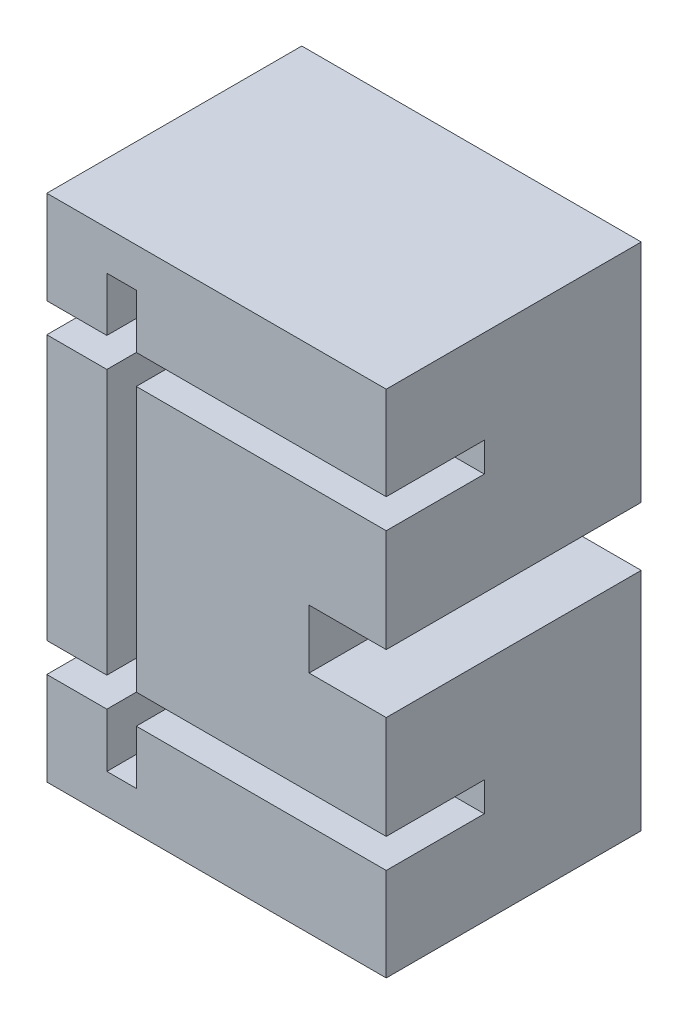
SolidWorks part; units mm, degrees
ref_plane "Ön Düzlem" through (0, 0, 0) normal (0, 0, 1) x (1, 0, 0)
ref_plane "Üst Düzlem" through (0, 0, 0) normal (0, 1, 0) x (1, 0, 0)
ref_plane "Sağ Düzlem" through (0, 0, 0) normal (1, 0, 0) x (0, 0, -1)
sketch "Sketch1" plane through (0, 0, 0) normal (0, 0, 1) x (1, 0, 0)
  line L0 (8.5625, 14.5) -> (-8.5625, 14.5)
  line L1 (8.5625, 14.5) -> (8.5625, 13)
  line L2 (8.5625, -14.5) -> (-8.5625, -14.5)
  line L3 (-8.5625, 14.5) -> (-8.5625, -14.5)
  line L4 (8.5625, 14.5) -> (-8.5625, -14.5) construction
  line L5 (8.5625, -14.5) -> (-8.5625, 14.5) construction
  line L6 (7.0625, 13) -> (-7.0625, 13)
  line L7 (-7.0625, 13) -> (-7.0625, -13)
  line L8 (7.0625, -13) -> (-7.0625, -13)
  line L9 (8.5625, -13) -> (8.5625, -14.5)
  line L10 (7.0625, -13) -> (8.5625, -13)
  line L11 (7.0625, 13) -> (8.5625, 13)
  line L12 (7.0625, 0) -> (8.5625, 0) construction
  line L13 (9.3125, 1.5) -> (6.3125, 1.5)
  line L14 (9.3125, 1.5) -> (9.3125, -1.5)
  line L15 (9.3125, -1.5) -> (6.3125, -1.5)
  line L16 (6.3125, 1.5) -> (6.3125, -1.5)
  line L17 (9.3125, 1.5) -> (6.3125, -1.5) construction
  line L18 (9.3125, -1.5) -> (6.3125, 1.5) construction
  line L19 (8.5625, 1.5) -> (8.5625, -1.5)
  line L20 (7.0625, 1.5) -> (7.0625, -1.5)
  line L21 (8.5625, -13) -> (10.2438, -13)
  line L22 (10.2438, -13) -> (10.2438, -1.5)
  line L23 (10.2438, -1.5) -> (9.3125, -1.5)
  line L24 (9.3125, 1.5) -> (10.2438, 1.5)
  line L25 (10.2438, 1.5) -> (10.2438, 13)
  line L26 (10.2438, 13) -> (8.5625, 13)
  point P0 (0, 0)
  point P13 (7.8125, 0)
  dimension "D1" = 29
  dimension "D2" = 3
extrude "Boss-Extrude1" add sketch "Sketch1" along normal blind 13 contours L25 L26 L11 L6 L7 L8 L10 L21 L22 L23 L15 L16 L13 L24
sketch "Sketch2" plane through (0, 0, 13) normal (0, 0, 1) x (1, 0, 0)
  line L1 (-7.0625, 8.25) -> (10.2438, 8.25)
  line L2 (-7.0625, 8.25) -> (-7.0625, 6.75)
  line L3 (-7.0625, 6.75) -> (10.2438, 6.75)
  line L4 (10.2438, 8.25) -> (10.2438, 6.75)
  line L5 (-7.0625, 8.25) -> (10.2438, 6.75) construction
  line L6 (-7.0625, 6.75) -> (10.2438, 8.25) construction
  line L7 (10.2438, 1.5) -> (10.2438, 13) construction
  line L8 (-7.0625, 13) -> (-7.0625, -13) construction
  line L9 (0, 0) -> (6.3125, 0) construction
  line L10 (6.3125, 1.5) -> (6.3125, -1.5) construction
  line L11 (-7.0625, -6.75) -> (10.2438, -8.25) construction
  line L12 (-7.0625, -8.25) -> (10.2438, -6.75) construction
  line L13 (10.2438, -8.25) -> (10.2438, -6.75)
  line L14 (-7.0625, -6.75) -> (10.2438, -6.75)
  line L15 (-7.0625, -8.25) -> (-7.0625, -6.75)
  line L16 (-7.0625, -8.25) -> (10.2438, -8.25)
  line L18 (-2.5, 11) -> (-4, 11)
  line L19 (-2.5, 11) -> (-2.5, -11)
  line L20 (-2.5, -11) -> (-4, -11)
  line L21 (-4, 11) -> (-4, -11)
  line L22 (-2.5, 11) -> (-4, -11) construction
  line L23 (-2.5, -11) -> (-4, 11) construction
  point P0 (1.5906, 7.5)
  point P18 (1.5906, -7.5)
  point P19 (-3.25, 0)
  line M1 (10.2438, 1.5) -> (10.2438, 13)
  line M3 (-7.0625, 13) -> (-7.0625, -13)
  line M5 (10.2438, -13) -> (10.2438, -1.5)
  dimension "D1" = 7.5
  dimension "D2" = 1.5
  dimension "D3" = 11
  dimension "D4" = 2.5
extrude "Cut-Extrude1" cut sketch "Sketch2" against normal blind 5 contours L1 L19 L3 M1 | L18 L21 L1 L19 | L21 L1 L3 M3 | L1 L21 L3 L19 | L3 L21 L14 L19 | L16 L21 L20 L19 | L14 L21 L16 L19 | L21 L14 L16 M3 | L14 L19 L16 M5
